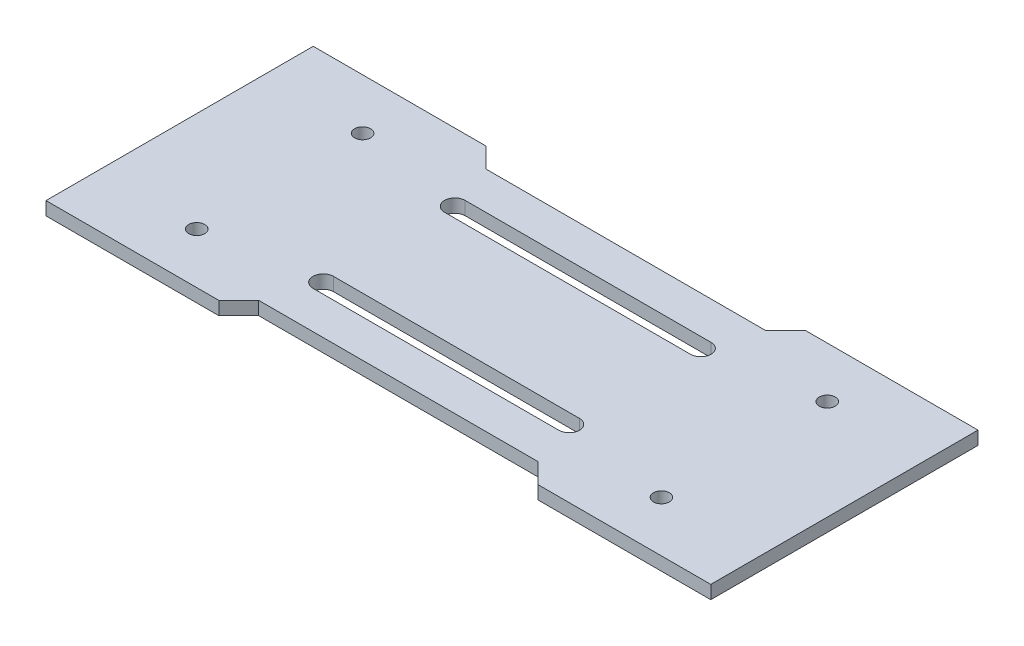
SolidWorks part; units mm, degrees
material "Thornel Mat VMA"
ref_plane "Front Plane" through (0, 0, 0) normal (0, 0, 1) x (1, 0, 0)
ref_plane "Top Plane" through (0, 0, 0) normal (0, 1, 0) x (1, 0, 0)
ref_plane "Right Plane" through (0, 0, 0) normal (1, 0, 0) x (0, 0, -1)
sketch "Sketch1" plane through (0, 0, 0) normal (0, 1, 0) x (1, 0, 0)
  line L0 (-50, 20.1) -> (-50, -20.1)
  line L1 (-50, -20.1) -> (-24, -20.1)
  line L2 (-24, -20.1) -> (-21, -17.1)
  line L3 (-21, -17.1) -> (21, -17.1)
  line L4 (21, -17.1) -> (24, -20.1)
  line L5 (24, -20.1) -> (50, -20.1)
  line L6 (50, -20.1) -> (50, 20.1)
  line L7 (50, 20.1) -> (24, 20.1)
  line L8 (24, 20.1) -> (21, 17.1)
  line L9 (21, 17.1) -> (-21, 17.1)
  line L10 (-21, 17.1) -> (-24, 20.1)
  line L11 (-24, 20.1) -> (-50, 20.1)
  line L12 (0, -55) -> (0, 55) construction
  line L13 (-55, 0) -> (55, 0) construction
  line L14 (-21, 17.1) -> (-21, -17.1) construction
  point P0 (0, 17.1)
  point P15 (-21, 0)
  point P17 (50, 0)
  point P20 (-50, 0)
  dimension "D1" = 40.2
  dimension "D2" = 100
  dimension "D3" = 42
  dimension "D4" = 34.2
extrude "Boss-Extrude1" add sketch "Sketch1" along normal mid plane 2
sketch "Sketch2" plane through (0, 1, 0) normal (0, 1, 0) x (1, 0, 0)
  line L0 (-18.5, 9.9) -> (18.5, 9.9) construction
  line L1 (-18.5, 11.45) -> (18.5, 11.45)
  line L2 (-18.5, 8.35) -> (18.5, 8.35)
  line L3 (-18.5, -9.9) -> (18.5, -9.9) construction
  line L4 (-18.5, -8.35) -> (18.5, -8.35)
  line L5 (-18.5, -11.45) -> (18.5, -11.45)
  line L7 (-34.95, 12.475) -> (34.95, 12.475) construction
  line L8 (-34.95, 12.475) -> (-34.95, -12.475) construction
  line L9 (-34.95, -12.475) -> (34.95, -12.475) construction
  line L10 (34.95, 12.475) -> (34.95, -12.475) construction
  line L12 (-1.1, 0) -> (1.1, 0) construction
  line L13 (0, -1.1) -> (0, 1.1) construction
  line L14 (0, 9.9) -> (0, -9.9) construction
  arc A0 (-18.5, 11.45) -> (-18.5, 8.35) centre (-18.5, 9.9) ccw
  arc A1 (18.5, 8.35) -> (18.5, 11.45) centre (18.5, 9.9) ccw
  arc A2 (-18.5, -8.35) -> (-18.5, -11.45) centre (-18.5, -9.9) ccw
  arc A3 (18.5, -11.45) -> (18.5, -8.35) centre (18.5, -9.9) ccw
  circle A4 centre (-34.95, 12.475) radius 1.2
  circle A5 centre (-34.95, -12.475) radius 1.2
  circle A6 centre (34.95, -12.475) radius 1.2
  circle A7 centre (34.95, 12.475) radius 1.2
  point P2 (0, 9.9)
  point P7 (0, -9.9)
  point P24 (-34.95, 0)
  point P25 (0, 12.475)
  point P28 (0, 0)
  dimension "D1" = 2.4
  dimension "D2" = 24.95
  dimension "D3" = 69.9
  dimension "D4" = 37
  dimension "D5" = 3.1
  dimension "D6" = 19.8
extrude "Cut-Extrude1" cut sketch "Sketch2" against normal through all both and the other way through all
